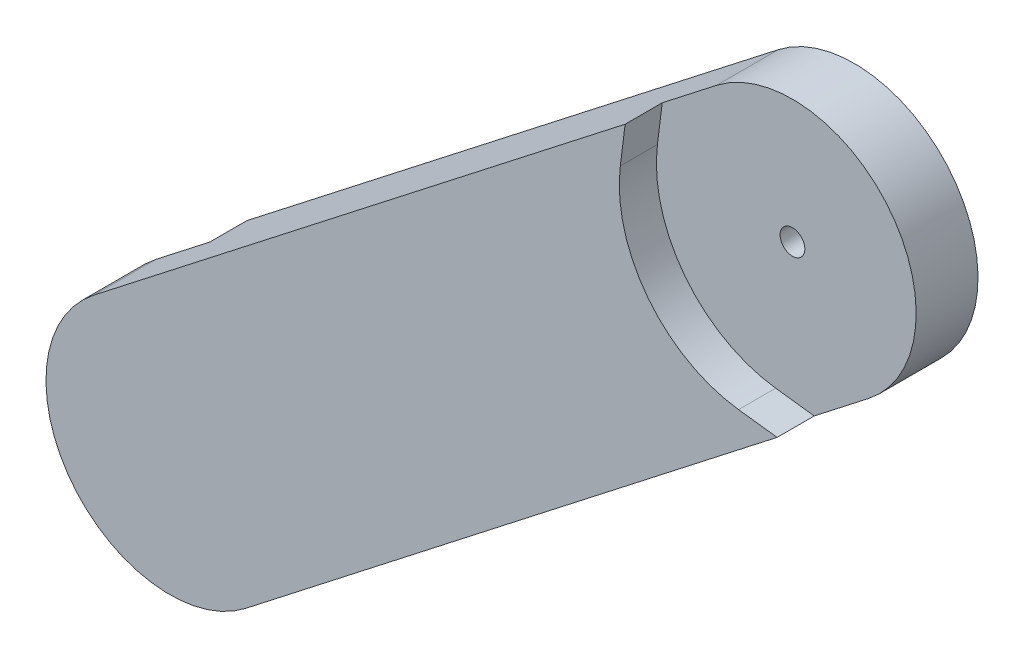
SolidWorks part; units mm, degrees
ref_plane "Front Plane" through (0, 0, 0) normal (0, 0, 1) x (1, 0, 0)
ref_plane "Top Plane" through (0, 0, 0) normal (0, 1, 0) x (1, 0, 0)
ref_plane "Right Plane" through (0, 0, 0) normal (1, 0, 0) x (0, 0, -1)
sketch "Sketch1" plane through (0, 0, 0) normal (0, 0, 1) x (1, 0, 0)
  line L0 (-15.3589, 19.7257) -> (102.9952, 111.8793)
  line L1 (15.3589, -19.7257) -> (133.7131, 72.4279)
  arc A0 (-15.3589, 19.7257) -> (15.3589, -19.7257) centre (0, 0) ccw
  arc A1 (133.7131, 72.4279) -> (102.9952, 111.8793) centre (118.3542, 92.1536) ccw
  dimension "D1" = 50
  dimension "D2" = 50
  dimension "D3" = 150
extrude "Boss-Extrude1" add sketch "Sketch1" along normal blind 20
sketch "Sketch2" plane through (0, 0, 0) normal (0, 0, -1) x (-1, 0, 0)
  arc A0 (-15.3589, -19.7257) -> (15.3589, 19.7257) centre (0, 0) ccw construction
  arc A1 (-15.3589, -19.7257) -> (15.3589, 19.7257) centre (0, 0) ccw
  circle A2 centre (0, 0) radius 25
  arc M1 (-15.3589, -19.7257) -> (15.3589, 19.7257) centre (0, 0) ccw
extrude "Cut-Extrude1" cut sketch "Sketch2" against normal blind 7.5 contours A2 M1
sketch "Sketch3" plane through (0, 0, 7.5) normal (0, 0, -1) x (-1, 0, 0)
  circle A0 centre (0, 0) radius 2.5
  dimension "D1" = 5
extrude "Cut-Extrude2" cut sketch "Sketch3" against normal blind 5
sketch "Sketch4" plane through (0, 0, 20) normal (0, 0, 1) x (1, 0, 0)
  circle A0 centre (118.3542, 92.1536) radius 25
  dimension "D1" = 50
extrude "Cut-Extrude3" cut sketch "Sketch4" against normal blind 7.5
sketch "Sketch5" plane through (0, 0, 0) normal (0, 0, -1) x (-1, 0, 0)
  line L0 (-26.3192, -11.1917) -> (-27.2894, -3.3965)
  line L1 (-32.9041, 25.62) -> (17.7841, -13.8471) construction
  line L2 (-15.3589, -19.7257) -> (-133.7131, 72.4279) construction
  line L3 (-15.3589, -19.7257) -> (-26.3192, -11.1917)
  line L4 (-3.3965, 27.2894) -> (4.3987, 28.2597)
  line L5 (-102.9952, 111.8793) -> (15.3589, 19.7257) construction
  line L6 (-102.9952, 111.8793) -> (15.3589, 19.7257)
  arc A0 (-3.3965, 27.2894) -> (-27.2894, -3.3965) centre (0, 0) ccw
  arc A1 (15.3589, 19.7257) -> (-15.3589, -19.7257) centre (0, 0) ccw construction
  arc A2 (15.3589, 19.7257) -> (-15.3589, -19.7257) centre (0, 0) ccw
  line M6 (-133.7131, 72.4279) -> (-15.3589, -19.7257)
  arc M7 (-15.3589, -19.7257) -> (15.3589, 19.7257) centre (0, 0) cw
  line M8 (15.3589, 19.7257) -> (-102.9952, 111.8793)
  dimension "D1" = 55
  dimension "D2" = 45
  dimension "D3" = 45
extrude "Cut-Extrude4" cut sketch "Sketch5" against normal blind 7.5 contours A0 L1 A2 L4 M8 | L1 A0 L0 M6 M7
sketch "Sketch6" plane through (0, 0, 20) normal (0, 0, 1) x (1, 0, 0)
  line L0 (80.9856, 63.0575) -> (118.3542, 92.1536)
  line L1 (114.9576, 64.8642) -> (143.4341, 61.3199)
  line L2 (91.0647, 95.5502) -> (92.0349, 103.3454)
  line L3 (15.3589, -19.7257) -> (133.7131, 72.4279) construction
  line L4 (102.9952, 111.8793) -> (-15.3589, 19.7257) construction
  line L5 (102.9952, 111.8793) -> (92.0349, 103.3454)
  line L6 (122.7528, 63.894) -> (133.7131, 72.4279)
  arc A0 (91.0647, 95.5502) -> (114.9576, 64.8642) centre (118.3542, 92.1536) ccw
  arc A1 (102.9952, 111.8793) -> (133.7131, 72.4279) centre (118.3542, 92.1536) ccw construction
  arc A2 (102.9952, 111.8793) -> (133.7131, 72.4279) centre (118.3542, 92.1536) ccw
  arc M5 (133.7131, 72.4279) -> (102.9952, 111.8793) centre (118.3542, 92.1536) cw
  line M6 (102.9952, 111.8793) -> (-15.3589, 19.7257)
  line M8 (15.3589, -19.7257) -> (133.7131, 72.4279)
  dimension "D1" = 55
  dimension "D2" = 45
  dimension "D3" = 45
extrude "Cut-Extrude5" cut sketch "Sketch6" against normal blind 7.5 and the other way through all contours L0 A0 L1 M8 M5 | L2 A0 L0 M5 M6
sketch "Sketch7" plane through (0, 0, 12.5) normal (0, 0, 1) x (1, 0, 0)
  circle A2 centre (118.3542, 92.1536) radius 2.5
  dimension "D1" = 5
extrude "Cut-Extrude6" cut sketch "Sketch7" against normal through all
